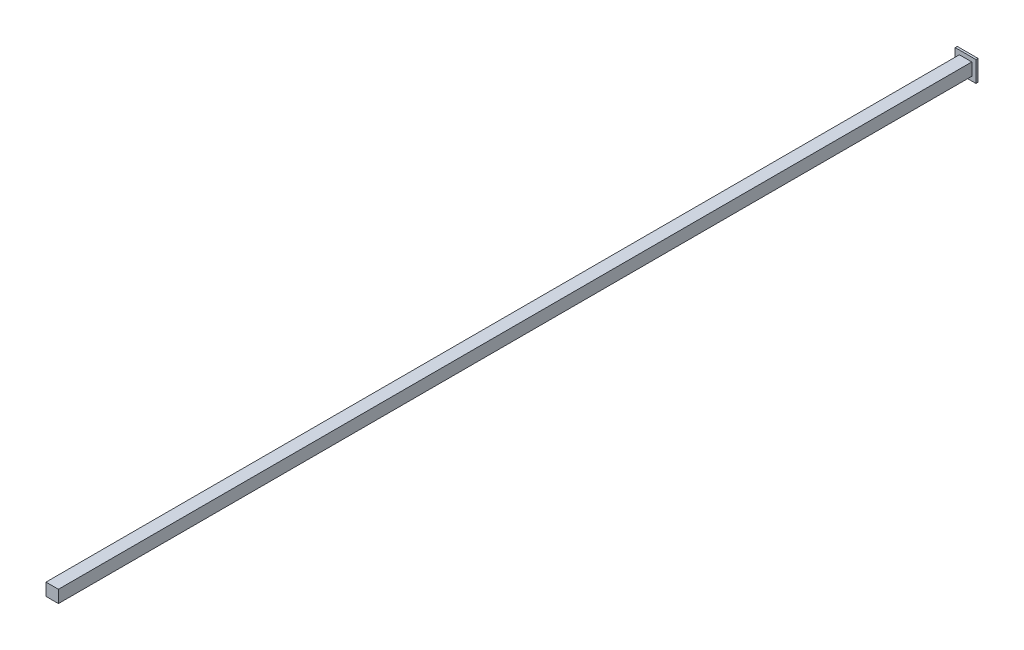
SolidWorks part; units mm, degrees
ref_plane "Piano frontale" through (0, 0, 0) normal (0, 0, 1) x (1, 0, 0)
ref_plane "Piano superiore" through (0, 0, 0) normal (0, 1, 0) x (1, 0, 0)
ref_plane "Piano destro" through (0, 0, 0) normal (1, 0, 0) x (0, 0, -1)
sketch "Schizzo1" plane through (0, 0, 0) normal (0, 0, 1) x (1, 0, 0)
  line L1 (-25, -25) -> (25, -25)
  line L2 (-25, -25) -> (-25, 25)
  line L3 (-25, 25) -> (25, 25)
  line L4 (25, -25) -> (25, 25)
  line L5 (-25, -25) -> (25, 25) construction
  line L6 (-25, 25) -> (25, -25) construction
  point P0 (0, 0)
  dimension "D1" = 50
  dimension "D2" = 50
extrude "Estrusione-Estrusione1" add sketch "Schizzo1" along normal blind 5
sketch "Schizzo2" plane through (0, 0, 5) normal (0, 0, 1) x (1, 0, 0)
  line L1 (-15, -15) -> (15, -15)
  line L2 (-15, -15) -> (-15, 15)
  line L3 (-15, 15) -> (15, 15)
  line L4 (15, -15) -> (15, 15)
  line L5 (-15, -15) -> (15, 15) construction
  line L6 (-15, 15) -> (15, -15) construction
  line L7 (-12, 12) -> (12, 12)
  line L8 (-12, 12) -> (-12, -12)
  line L9 (-12, -12) -> (12, -12)
  line L10 (12, 12) -> (12, -12)
  line L11 (-12, 12) -> (12, -12) construction
  line L12 (-12, -12) -> (12, 12) construction
  point P0 (0, 0)
  point P6 (0, 0)
  dimension "D1" = 30
  dimension "D2" = 30
  dimension "D3" = 24
  dimension "D4" = 24
extrude "Estrusione-Estrusione2" add sketch "Schizzo2" along normal blind 2205
sketch "Schizzo3" plane through (0, 0, 2210) normal (0, 0, 1) x (1, 0, 0)
  line L1 (-12, 12) -> (12, 12)
  line L2 (-12, 12) -> (-12, -12)
  line L3 (-12, -12) -> (12, -12)
  line L4 (12, 12) -> (12, -12)
  line L5 (-12, 12) -> (12, -12) construction
  line L6 (-12, -12) -> (12, 12) construction
  point P0 (0, 0)
extrude "Estrusione-Estrusione3" add sketch "Schizzo3" against normal blind 5
